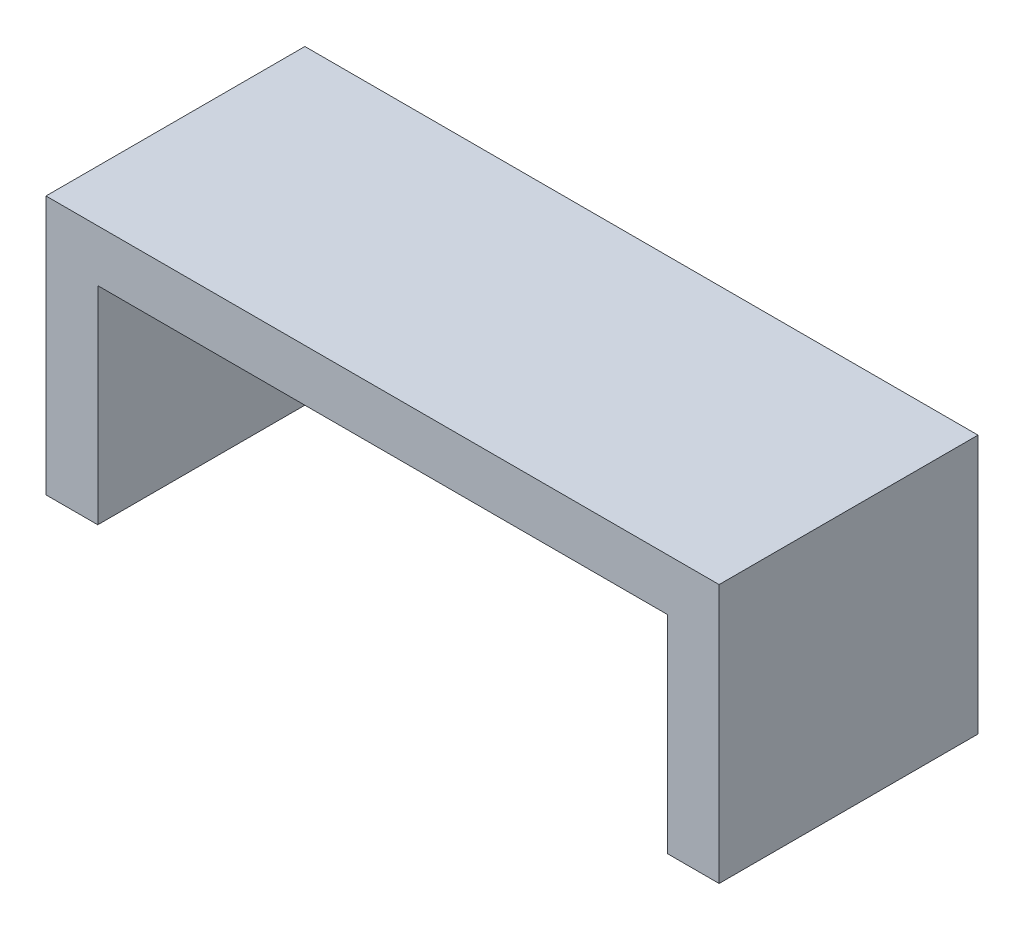
SolidWorks part; units mm, degrees
ref_plane "正面" through (0, 0, 0) normal (0, 0, 1) x (1, 0, 0)
ref_plane "平面" through (0, 0, 0) normal (0, 1, 0) x (1, 0, 0)
ref_plane "右側面" through (0, 0, 0) normal (1, 0, 0) x (0, 0, -1)
sketch "ｽｹｯﾁ1" plane through (0, 0, 0) normal (0, 1, 0) x (1, 0, 0)
  line L0 (-27.5, 0) -> (27.5, 0) construction
  line L1 (-27.5, 0) -> (-39.1737, 0) construction
  line L2 (0, 0) -> (0, 19.1435) construction
  line L3 (27.5, 12.5) -> (27.5, -12.5)
  line L4 (-32.5, 12.5) -> (-27.5, 12.5)
  line L5 (-32.5, 12.5) -> (-32.5, -12.5)
  line L6 (-32.5, -12.5) -> (-27.5, -12.5)
  line L7 (-27.5, 12.5) -> (-27.5, -12.5)
  line L8 (-32.5, 12.5) -> (-27.5, -12.5) construction
  line L9 (-32.5, -12.5) -> (-27.5, 12.5) construction
  line L14 (32.5, 12.5) -> (27.5, 12.5)
  line L15 (32.5, 12.5) -> (32.5, -12.5)
  line L16 (32.5, -12.5) -> (27.5, -12.5)
  point P3 (-30, 0)
  dimension "D1" = 55
  dimension "D2" = 5
  dimension "D3" = 25
extrude "ﾎﾞｽ - 押し出し1" add sketch "ｽｹｯﾁ1" along normal blind 20
sketch "ｽｹｯﾁ2" plane through (0, 20, 0) normal (0, 1, 0) x (1, 0, 0)
  line L1 (-32.5, 12.5) -> (32.5, 12.5)
  line L2 (-32.5, 12.5) -> (-32.5, -12.5)
  line L3 (-32.5, -12.5) -> (32.5, -12.5)
  line L4 (32.5, 12.5) -> (32.5, -12.5)
extrude "ﾎﾞｽ - 押し出し2" add sketch "ｽｹｯﾁ2" along normal blind 5
